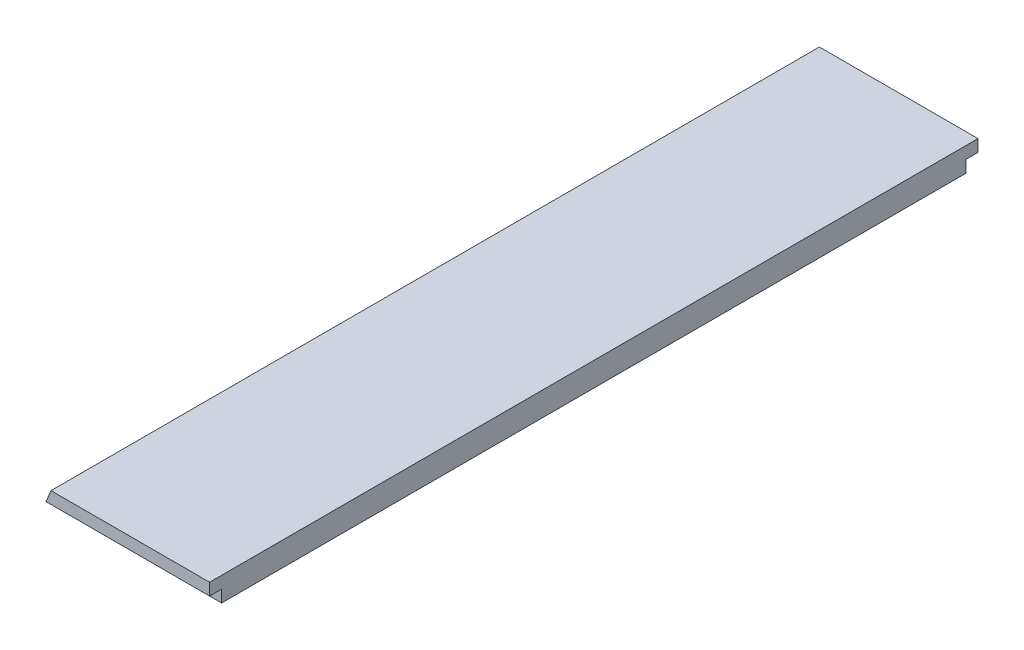
SolidWorks part; units mm, degrees
ref_plane "Front Plane" through (0, 0, 0) normal (0, 0, 1) x (1, 0, 0)
ref_plane "Top Plane" through (0, 0, 0) normal (0, 1, 0) x (1, 0, 0)
ref_plane "Right Plane" through (0, 0, 0) normal (1, 0, 0) x (0, 0, -1)
sketch "Sketch1" plane through (0, 0, 0) normal (0, 0, 1) x (1, 0, 0)
  line L0 (0, 0) -> (5.2605, 12.7)
  line L1 (5.2605, 12.7) -> (89.154, 12.7)
  line L2 (89.154, 12.7) -> (89.154, 0)
  line L3 (89.154, 0) -> (0, 0)
  dimension "D1" = 12.7
  dimension "D2" = 89.154
  dimension "D3" = 67.5
extrude "Boss-Extrude1" add sketch "Sketch1" along normal blind 406.4
sketch "Sketch2" plane through (0, 0, 0) normal (0, -1, 0) x (1, 0, 0)
  line L0 (0, 406.4) -> (0, 0) construction
  line L1 (0, 6.35) -> (89.154, 6.35)
  line L2 (0, 6.35) -> (0, 0)
  line L3 (0, 0) -> (89.154, 0)
  line L4 (89.154, 6.35) -> (89.154, 0)
  line L5 (89.154, 406.4) -> (89.154, 0) construction
  line L6 (0, 406.4) -> (89.154, 406.4)
  line L7 (0, 406.4) -> (0, 400.05)
  line L8 (0, 400.05) -> (89.154, 400.05)
  line L9 (89.154, 406.4) -> (89.154, 400.05)
  dimension "D1" = 6.35
  dimension "D2" = 6.35
extrude "Cut-Extrude1" cut sketch "Sketch2" against normal blind 6.35
